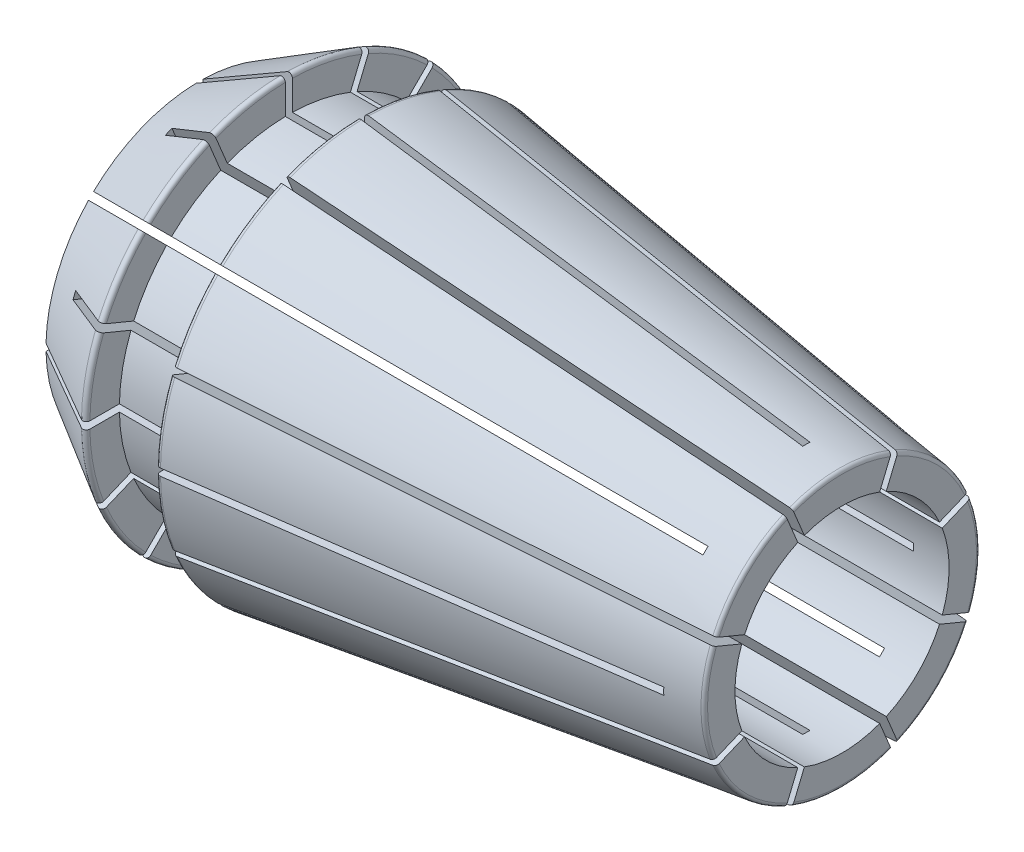
SolidWorks part; units mm, degrees
ref_plane "Front Plane" through (0, 0, 0) normal (0, 0, 1) x (1, 0, 0)
ref_plane "Top Plane" through (0, 0, 0) normal (0, 1, 0) x (1, 0, 0)
ref_plane "Right Plane" through (0, 0, 0) normal (1, 0, 0) x (0, 0, -1)
sketch "Sketch2" plane through (0, 0, 0) normal (1, 0, 0) x (0, 0, -1)
  circle A0 centre (0, 0) radius 5.75
  dimension "D1" = 11.5
extrude "Boss-Extrude1" add sketch "Sketch2" along normal blind 18
sketch "Sketch3" plane through (0, 0, 0) normal (0, 0, 1) x (1, 0, 0)
  line L0 (0, 0) -> (132.04, 0) construction
  line L1 (0, 4.3066) -> (2.5, 5.75)
  line L2 (0, 5.75) -> (0, -5.75) construction
  line L4 (2.5, 5.75) -> (2.5, 4.75)
  line L5 (2.5, 4.75) -> (4.5212, 4.75)
  line L6 (4.5212, 4.75) -> (4.5212, 5.75)
  line L7 (4.5212, 5.75) -> (18, 3.8557)
  line L8 (18, -5.75) -> (18, 5.75) construction
  line L9 (18, 3.8557) -> (18, 10.75)
  line L10 (18, 10.75) -> (0, 10.75)
  line L11 (0, 10.75) -> (0, 4.3066)
  line L13 (18, 5.75) -> (0, 5.75) construction
  line L15 (0, 0) -> (18, 0)
  line L16 (0, 0) -> (0, 3)
  line L17 (0, 3) -> (18, 3)
  line L18 (18, 0) -> (18, 3)
  point P9 (6.3, 5.5)
  point P21 (4.5212, 5.25)
  dimension "D1" = 30
  dimension "D2" = 8
  dimension "D3" = 9.5
  dimension "D4" = 2.5
  dimension "D5" = 3.8
  dimension "D6" = 11
  dimension "D7" = 6
  dimension "D8" = 11.5
  dimension "D9" = 2.0212
  dimension "D10" = 5
  dimension "D11" = 18
  dimension "D12" = 13.4788
  dimension "D13" = 3.8
revolve "Cut-Revolve1" cut sketch "Sketch3" angle 360 about L0
sketch "Sketch4" plane through (0, 0, 0) normal (-1, 0, 0) x (0, 0, 1)
  line L0 (21.8496, 21.991) -> (21.991, 21.8496)
  line L1 (-0.1, 31) -> (0.1, 31)
  line L2 (-0.1, 31) -> (-0.1, -31)
  line L3 (-0.1, -31) -> (0.1, -31)
  line L4 (0.1, 31) -> (0.1, -31)
  line L5 (-0.1, 31) -> (0.1, -31) construction
  line L6 (-0.1, -31) -> (0.1, 31) construction
  line L7 (21.8496, 21.991) -> (-21.991, -21.8496)
  line L8 (-21.991, -21.8496) -> (-21.8496, -21.991)
  line L9 (21.991, 21.8496) -> (-21.8496, -21.991)
  line L10 (21.8496, 21.991) -> (-21.8496, -21.991) construction
  line L11 (-21.991, -21.8496) -> (21.991, 21.8496) construction
  line L12 (31, 0.1) -> (31, -0.1)
  line L13 (31, 0.1) -> (-31, 0.1)
  line L14 (-31, 0.1) -> (-31, -0.1)
  line L15 (31, -0.1) -> (-31, -0.1)
  line L16 (31, 0.1) -> (-31, -0.1) construction
  line L17 (-31, 0.1) -> (31, -0.1) construction
  line L18 (21.991, -21.8496) -> (21.8496, -21.991)
  line L19 (21.991, -21.8496) -> (-21.8496, 21.991)
  line L20 (-21.8496, 21.991) -> (-21.991, 21.8496)
  line L21 (21.8496, -21.991) -> (-21.991, 21.8496)
  line L22 (21.991, -21.8496) -> (-21.991, 21.8496) construction
  line L23 (-21.8496, 21.991) -> (21.8496, -21.991) construction
  line L24 (0.1, -31) -> (-0.1, -31)
  line L25 (0.1, -31) -> (0.1, 31)
  line L26 (0.1, 31) -> (-0.1, 31)
  line L27 (-0.1, -31) -> (-0.1, 31)
  line L28 (0.1, -31) -> (-0.1, 31) construction
  line L29 (0.1, 31) -> (-0.1, -31) construction
  line L30 (-21.8496, -21.991) -> (-21.991, -21.8496)
  line L31 (-21.8496, -21.991) -> (21.991, 21.8496)
  line L32 (21.991, 21.8496) -> (21.8496, 21.991)
  line L33 (-21.991, -21.8496) -> (21.8496, 21.991)
  line L34 (-21.8496, -21.991) -> (21.8496, 21.991) construction
  line L35 (21.991, 21.8496) -> (-21.991, -21.8496) construction
  line L36 (-31, -0.1) -> (-31, 0.1)
  line L37 (-31, -0.1) -> (31, -0.1)
  line L38 (31, -0.1) -> (31, 0.1)
  line L39 (-31, 0.1) -> (31, 0.1)
  line L40 (-31, -0.1) -> (31, 0.1) construction
  line L41 (31, -0.1) -> (-31, 0.1) construction
  line L42 (-21.991, 21.8496) -> (-21.8496, 21.991)
  line L43 (-21.991, 21.8496) -> (21.8496, -21.991)
  line L44 (21.8496, -21.991) -> (21.991, -21.8496)
  line L45 (-21.8496, 21.991) -> (21.991, -21.8496)
  line L46 (-21.991, 21.8496) -> (21.991, -21.8496) construction
  line L47 (21.8496, -21.991) -> (-21.8496, 21.991) construction
  point P0 (0, 0)
  point P37 (0, 0)
  dimension "D3" = 31
  dimension "D1" = 0.2
  dimension "D2" = 8
extrude "Cut-Extrude1" cut sketch "Sketch4" against normal offset from surface (17 mm away) 1 contours L19 L20 L21 L18 | L13 L14 L15 L12 | L7 L8 L9 L0 | L4 L3 L2 L1 up to face at (18, 0, 3)
sketch "Sketch5" plane through (18, 0, 0) normal (1, 0, 0) x (0, 0, -1)
  line L0 (0, 0) -> (0, -5.7107) construction
  line L1 (-11.9556, -28.602) -> (-11.7708, -28.6785)
  line L2 (-11.9556, -28.602) -> (11.7708, 28.6785)
  line L3 (11.7708, 28.6785) -> (11.9556, 28.602)
  line L4 (-11.7708, -28.6785) -> (11.9556, 28.602)
  line L5 (-11.9556, -28.602) -> (11.9556, 28.602) construction
  line L6 (11.7708, 28.6785) -> (-11.7708, -28.6785) construction
  line L7 (28.602, 11.9556) -> (28.6785, 11.7708)
  line L8 (-28.602, -11.9556) -> (28.6785, 11.7708)
  line L9 (-28.6785, -11.7708) -> (28.602, 11.9556)
  line L10 (-28.6785, -11.7708) -> (-28.602, -11.9556)
  line L11 (28.6785, -11.7708) -> (28.602, -11.9556)
  line L12 (-28.6785, 11.7708) -> (28.602, -11.9556)
  line L13 (-28.602, 11.9556) -> (28.6785, -11.7708)
  line L14 (-28.602, 11.9556) -> (-28.6785, 11.7708)
  line L15 (11.9556, -28.602) -> (11.7708, -28.6785)
  line L16 (-11.9556, 28.602) -> (11.7708, -28.6785)
  line L17 (-11.7708, 28.6785) -> (11.9556, -28.602)
  line L18 (-11.7708, 28.6785) -> (-11.9556, 28.602)
  line L19 (-11.7708, -28.6785) -> (-11.9556, -28.602)
  line L20 (11.7708, 28.6785) -> (-11.9556, -28.602)
  line L21 (11.9556, 28.602) -> (-11.7708, -28.6785)
  line L22 (11.9556, 28.602) -> (11.7708, 28.6785)
  line L23 (-28.602, -11.9556) -> (-28.6785, -11.7708)
  line L24 (28.602, 11.9556) -> (-28.6785, -11.7708)
  line L25 (28.6785, 11.7708) -> (-28.602, -11.9556)
  line L26 (28.6785, 11.7708) -> (28.602, 11.9556)
  line L27 (-28.6785, 11.7708) -> (-28.602, 11.9556)
  line L28 (28.6785, -11.7708) -> (-28.602, 11.9556)
  line L29 (28.602, -11.9556) -> (-28.6785, 11.7708)
  line L30 (28.602, -11.9556) -> (28.6785, -11.7708)
  line L31 (-11.9556, 28.602) -> (-11.7708, 28.6785)
  line L32 (11.9556, -28.602) -> (-11.7708, 28.6785)
  line L33 (11.7708, -28.6785) -> (-11.9556, 28.602)
  line L34 (11.7708, -28.6785) -> (11.9556, -28.602)
  point P0 (0, 0)
  point P40 (0, 0)
  dimension "D1" = 0.2
  dimension "D2" = 22.5
  dimension "D3" = 8
extrude "Cut-Extrude2" cut sketch "Sketch5" against normal offset from surface (17 mm away) 1 contours L8 L7 L9 L10 | L12 L11 L13 L14 | L16 L15 L17 L18 | L4 L3 L2 L1 up to face at (0, 3.2638, 1.3519)
chamfer "Фаска1" distance 0.1 angle 60 8 edges at (0, -1.1481, -2.7716) (0, -2.7716, -1.1481) (0, -2.7716, 1.1481) (0, -1.1481, 2.7716) (0, 1.1481, 2.7716) (0, 2.7716, 1.1481) (0, 2.7716, -1.1481) (0, 1.1481, -2.7716)
fillet "Скругление1" radius 0.1 40 edges at (18, -2.7264, -2.7264) (18, 0, -3.8557) (18, 2.7264, -2.7264) (18, 3.8557, 0) (18, -3.8557, 0) (18, -2.7264, 2.7264) (18, 0, 3.8557) (18, 2.7264, 2.7264) (4.5212, 1.1218, -5.6395) (4.5212, 3.1945, -4.781) (4.5212, 4.781, -3.1945) (2.5, 4.781, -3.1945) (2.5, 3.1945, -4.781) (2.5, 1.1218, -5.6395) (4.5212, -4.781, -3.1945) (4.5212, -3.1945, -4.781) (4.5212, -1.1218, -5.6395) (2.5, -1.1218, -5.6395) (2.5, -3.1945, -4.781) (2.5, -4.781, -3.1945) (4.5212, -5.6395, -1.1218) (2.5, -5.6395, -1.1218) (2.5, -5.6395, 1.1218) (4.5212, -5.6395, 1.1218) (2.5, -4.781, 3.1945) (2.5, -3.1945, 4.781) (2.5, -1.1218, 5.6395) (4.5212, -4.781, 3.1945) (4.5212, -3.1945, 4.781) (4.5212, -1.1218, 5.6395) (4.5212, 1.1218, 5.6395) (2.5, 5.6395, -1.1218) (4.5212, 5.6395, -1.1218) (4.5212, 5.6395, 1.1218) (2.5, 5.6395, 1.1218) (2.5, 4.781, 3.1945) (2.5, 1.1218, 5.6395) (2.5, 3.1945, 4.781) (4.5212, 4.781, 3.1945) (4.5212, 3.1945, 4.781)
equation "\"L\"= 13.5"
